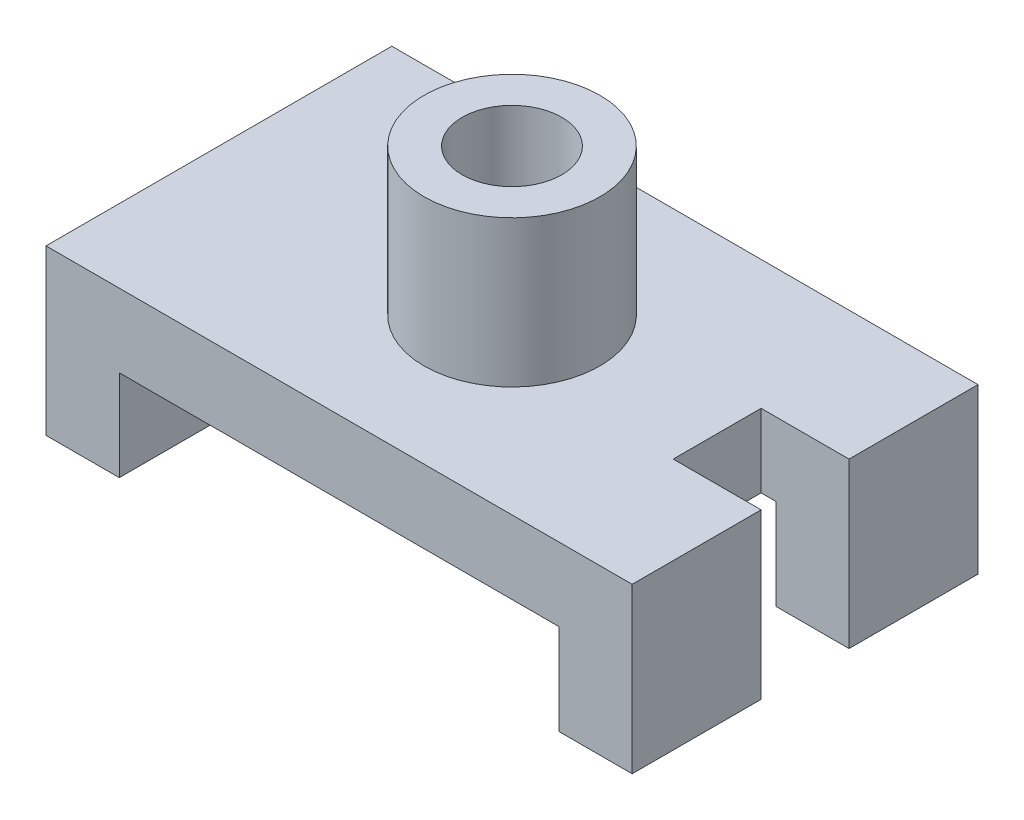
SolidWorks part; units mm, degrees
ref_plane "Alzado" through (0, 0, 0) normal (0, 0, 1) x (1, 0, 0)
ref_plane "Planta" through (0, 0, 0) normal (0, 1, 0) x (1, 0, 0)
ref_plane "Vista lateral" through (0, 0, 0) normal (1, 0, 0) x (0, 0, -1)
sketch "Croquis1" plane through (0, 0, 0) normal (0, 0, 1) x (1, 0, 0)
  line L0 (1.5, -0.62) -> (2, -0.62)
  line L1 (-2, 0.5) -> (2, 0.5)
  line L2 (-2, 0.5) -> (-2, -0.62)
  line L3 (-2, -0.62) -> (-1.5, -0.62)
  line L4 (2, 0.5) -> (2, -0.62)
  line L6 (-1.5, -0.62) -> (-1.5, 0)
  line L7 (-1.5, 0) -> (1.5, 0)
  line L8 (1.5, -0.62) -> (1.5, 0)
  point P8 (0, 0)
  point P10 (0, 0.5)
  dimension "D1" = 1.12
  dimension "D2" = 0.5
  dimension "D3" = 3
  dimension "D4" = 4
extrude "Saliente-Extruir1" add sketch "Croquis1" against normal blind 2.36
sketch "Croquis2" plane through (0, 0.5, 0) normal (0, 1, 0) x (1, 0, 0)
  line L0 (2, 2.36) -> (2, 0) construction
  line L1 (2, 1.48) -> (1.4, 1.48)
  line L2 (2, 1.48) -> (2, 0.88)
  line L3 (2, 0.88) -> (1.4, 0.88)
  line L4 (1.4, 1.48) -> (1.4, 0.88)
  line L5 (2, 2.36) -> (-2, 2.36) construction
  dimension "D1" = 0.6
  dimension "D2" = 0.88
extrude "Cortar-Extruir2" cut sketch "Croquis2" against normal through all
sketch "Croquis3" plane through (0, 0.5, 0) normal (0, 1, 0) x (1, 0, 0)
  line L0 (-2, 2.36) -> (-2, 0) construction
  line L1 (2, 2.36) -> (-2, 2.36) construction
  circle A0 centre (0, 1.18) radius 0.6
  circle A1 centre (0, 1.18) radius 0.34
  point P3 (0, 0)
  point P6 (-2, 1.18)
  point P9 (0, 2.36)
  dimension "D1" = 1.2
  dimension "D2" = 0.68
extrude "Saliente-Extruir2" add sketch "Croquis3" along normal blind 1
